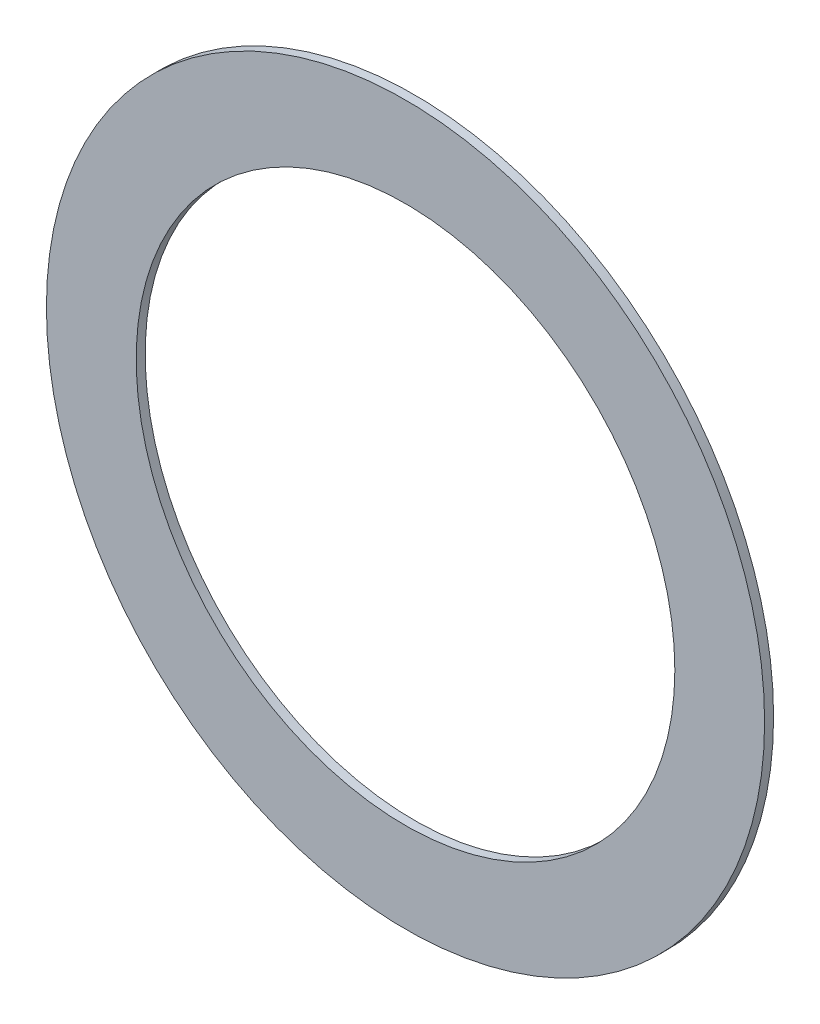
SolidWorks part; units mm, degrees
ref_plane "前视基准面" through (0, 0, 0) normal (0, 0, 1) x (1, 0, 0)
ref_plane "上视基准面" through (0, 0, 0) normal (0, 1, 0) x (1, 0, 0)
ref_plane "右视基准面" through (0, 0, 0) normal (1, 0, 0) x (0, 0, -1)
sketch "草图1" plane through (0, 0, 0) normal (0, 0, 1) x (1, 0, 0)
  circle A0 centre (0, 0) radius 6
  circle A1 centre (0, 0) radius 8
  dimension "D1" = 12
  dimension "D2" = 16
extrude "凸台-拉伸1" add sketch "草图1" along normal mid plane 0.2
